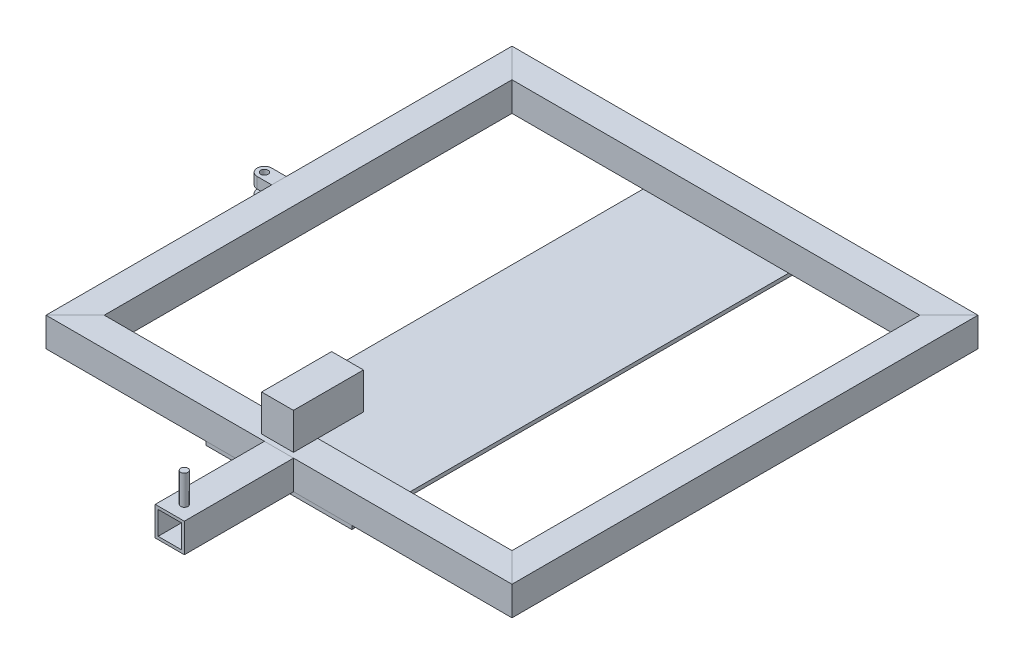
SolidWorks part; units mm, degrees
material "AISI 1020"
ref_plane "Alzado" through (0, 0, 0) normal (0, 0, 1) x (1, 0, 0)
ref_plane "Planta" through (0, 0, 0) normal (0, 1, 0) x (1, 0, 0)
ref_plane "Vista lateral" through (0, 0, 0) normal (1, 0, 0) x (0, 0, -1)
sketch "Croquis1" plane through (0, 0, 0) normal (0, 1, 0) x (1, 0, 0)
  line L0 (0, -150) -> (0, -200)
  line L1 (-150, 150) -> (150, 150)
  line L2 (-150, 150) -> (-150, -150)
  line L3 (-150, -150) -> (150, -150)
  line L4 (150, 150) -> (150, -150)
  line L5 (-150, 150) -> (150, -150) construction
  line L6 (-150, -150) -> (150, 150) construction
  point P0 (0, 0)
  dimension "D1" = 300
  dimension "D2" = 300
  dimension "D3" = 50
other "Tubo cuadrado 20 X 20 X 2(2)"
ref_plane "Plano2" through (-150, 0, -150) normal (0, 0, 1) x (1, 0, 0)
sketch "Sketch1" plane through (-150, 0, -150) normal (0, 0, 1) x (1, 0, 0)
  line L2 (10, 10) -> (-10, 10)
  line L3 (10, 10) -> (10, -10)
  line L4 (10, -10) -> (-10, -10)
  line L5 (-10, 10) -> (-10, -10)
  line L6 (10, 10) -> (-10, -10) construction
  line L7 (10, -10) -> (-10, 10) construction
  line L8 (-8, 8) -> (8, 8)
  line L9 (-8, 8) -> (-8, -8)
  line L10 (-8, -8) -> (8, -8)
  line L11 (8, 8) -> (8, -8)
  line L12 (-8, 8) -> (8, -8) construction
  line L13 (-8, -8) -> (8, 8) construction
  point P0 (0, 0)
  point P5 (0, 0)
  dimension "D1" = 20
  dimension "D2" = 20
  dimension "D3" = 2
ref_plane "Plano3" through (0, -10, 0) normal (0, 1, 0) x (1, 0, 0)
sketch "Croquis3" plane through (0, -10, 0) normal (0, 1, 0) x (1, 0, 0)
  line L0 (160, -160) -> (-160, -160) construction
  line L1 (-50, 160) -> (50, 160)
  line L2 (-50, 160) -> (-50, -160)
  line L3 (-50, -160) -> (50, -160)
  line L4 (50, 160) -> (50, -160)
  line L5 (-50, 160) -> (50, -160) construction
  line L6 (-50, -160) -> (50, 160) construction
  point P0 (0, 0)
  dimension "D1" = 100
extrude "Saliente-Extruir1" add sketch "Croquis3" against normal blind 2.5 separate body
sketch "Croquis4" plane through (0, -10, 0) normal (0, -1, 0) x (1, 0, 0)
  line L0 (0, 0) -> (0, 150) construction
  line L1 (0, 150) -> (-85.4, 150) construction
  line L2 (-72.9865, 0) -> (105.8656, 0) construction
  circle A0 centre (-85.4, 150) radius 1.2
  circle A1 centre (85.4, 150) radius 1.2
  circle A2 centre (85.4, -150) radius 1.2
  circle A3 centre (-85.4, -150) radius 1.2
  dimension "D3" = 2.4
  dimension "D1" = 150
  dimension "D2" = 85.4
sketch "Croquis5" plane through (0, 10, 0) normal (0, 1, 0) x (1, 0, 0)
  line L0 (140, -140) -> (160, -160) construction
  line L1 (-150, 150) -> (150, 150)
  line L2 (-150, 150) -> (-150, -150)
  line L3 (-150, -150) -> (150, -150)
  line L4 (150, 150) -> (150, -150)
  line L5 (-150, 150) -> (150, -150) construction
  line L6 (-150, -150) -> (150, 150) construction
  line L7 (0, 0) -> (-150, 0) construction
  line L8 (-150, 0) -> (-150, -112.5) construction
  line L9 (0, 116.369) -> (0, -62.2851) construction
  circle A0 centre (-150, -112.5) radius 1.7
  circle A1 centre (150, -112.5) radius 1.7
  circle A2 centre (-150, 112.5) radius 1.7
  circle A3 centre (150, 112.5) radius 1.7
  point P0 (0, 0)
  point P14 (150, -112.5)
  point P16 (150, 112.5)
  point P17 (-150, 112.5)
  dimension "D2" = 3.4
  dimension "D1" = 37.5
sketch "Croquis6" plane through (-160, 0, 0) normal (-1, 0, 0) x (0, 0, 1)
  line L0 (-65.676, 0) -> (61.5605, 0) construction
ref_plane "Plano4" through (0, 10, 0) normal (0, 1, 0) x (1, 0, 0)
sketch "Croquis7" plane through (0, 10, 0) normal (0, 1, 0) x (1, 0, 0)
  line L0 (0, 0) -> (-160, 0) construction
  line L1 (-160, -160) -> (-160, 160) construction
  line L2 (-160, 0) -> (-160, 5)
  line L3 (-160, 5) -> (-170, 5)
  line L4 (-170, -5) -> (-160, -5)
  line L5 (-160, 0) -> (-160, -5)
  arc A0 (-170, 5) -> (-170, -5) centre (-170, 0) ccw
  circle A1 centre (-170, 0) radius 2.5
  dimension "D3" = 5
  dimension "D4" = 10
  dimension "D1" = 5
  dimension "D2" = 5
extrude "Saliente-Extruir2" add sketch "Croquis7" against normal up to surface (20 mm away) separate body up to face at (-150, -10, 0)
sketch "Croquis9" plane through (0, 0, 5) normal (0, 0, 1) x (1, 0, 0)
  line L0 (-160, 10) -> (-160, 0) construction
  line L1 (-160, -10) -> (-160, 10) construction
  line L2 (-160, 0) -> (-160, 2.5) construction
  line L11 (-160, 0) -> (-160, -2.5) construction
  line L12 (-160, 2.5) -> (-165, 2.5) construction
  line L13 (-165, 2.5) -> (-177.5142, 2.5)
  line L14 (-160, -2.5) -> (-165, -2.5) construction
  line L15 (-165, -2.5) -> (-177.5142, -2.5)
  line L16 (-177.5142, -2.5) -> (-177.5142, 2.5)
  line L17 (-165, 2.5) -> (-165, -2.5)
  dimension "D1" = 2.5
  dimension "D2" = 2.5
  dimension "D3" = 5
extrude "Cortar-Extruir1" cut sketch "Croquis9" against normal blind 33
sketch "Croquis10" plane through (0, 0, 0) normal (0, 1, 0) x (1, 0, 0)
  line L0 (0, 0) -> (0, -160) construction
  line L1 (160, -160) -> (-160, -160) construction
  line L2 (0, -160) -> (0, -235)
  dimension "D1" = 75
other "Tubo cuadrado 20 X 20 X 2(4)"
ref_plane "Plano5" through (0, 0, 160) normal (0, 0, 1) x (1, 0, 0)
sketch "Sketch11" plane through (0, 0, 160) normal (0, 0, 1) x (1, 0, 0)
  line L0 (-6, -8) -> (6, -8)
  line L1 (-8, -6) -> (-8, 6)
  line L2 (6, 8) -> (-6, 8)
  line L3 (8, 6) -> (8, -6)
  line L4 (-6, -10) -> (6, -10)
  line L5 (-10, -6) -> (-10, 6)
  line L6 (6, 10) -> (-6, 10)
  line L7 (10, 6) -> (10, -6)
  line L8 (-10, 6) -> (-10, 10)
  line L9 (-10, 10) -> (-6, 10)
  line L10 (-8, 6) -> (-8, 8)
  line L11 (-8, 8) -> (-6, 8)
  line L12 (8, 6) -> (8, 8)
  line L13 (8, 8) -> (6, 8)
  line L14 (6, 10) -> (10, 10)
  line L15 (10, 10) -> (10, 6)
  line L16 (6, -8) -> (8, -8)
  line L17 (8, -8) -> (8, -6)
  line L18 (10, -6) -> (10, -10)
  line L19 (10, -10) -> (6, -10)
  line L20 (-8, -6) -> (-8, -8)
  line L21 (-8, -8) -> (-6, -8)
  line L22 (-10, -6) -> (-10, -10)
  line L23 (-10, -10) -> (-6, -10)
  point P0 (-10, 0)
  point P1 (10, 0)
  point P2 (0, 10)
  point P3 (0, -10)
  point P4 (0, 0)
  point P5 (-10, -10)
  point P6 (10, -10)
  point P7 (10, 10)
  point P8 (-10, 10)
  point P33 (0, 0)
  dimension "Thickness" = 2
  dimension "V_leg" = 20
sketch "Croquis12" plane through (0, 10, 0) normal (0, 1, 0) x (1, 0, 0)
  line L0 (0, -235) -> (0, -225) construction
  line L1 (0, -160) -> (0, -235) construction
  circle A0 centre (0, -225) radius 2.5
  dimension "D1" = 5
  dimension "D2" = 10
extrude "Saliente-Extruir3" add sketch "Croquis12" along normal blind 20.3 separate body
sketch "Croquis13" plane through (0, 30.3, 0) normal (0, 1, 0) x (1, 0, 0)
  line L0 (0, -225) -> (5, -225) construction
  line L1 (5, -225) -> (5, -128.8597) construction
  line L3 (5, -128.8597) -> (26.8594, -128.8597)
  line L4 (5, -128.8597) -> (5, -176.9299)
  line L5 (5, -176.9299) -> (26.8594, -176.9299)
  line L6 (26.8594, -128.8597) -> (26.8594, -176.9299)
  dimension "D1" = 5
extrude "Saliente-Extruir4" add sketch "Croquis13" along normal blind 25 separate body
